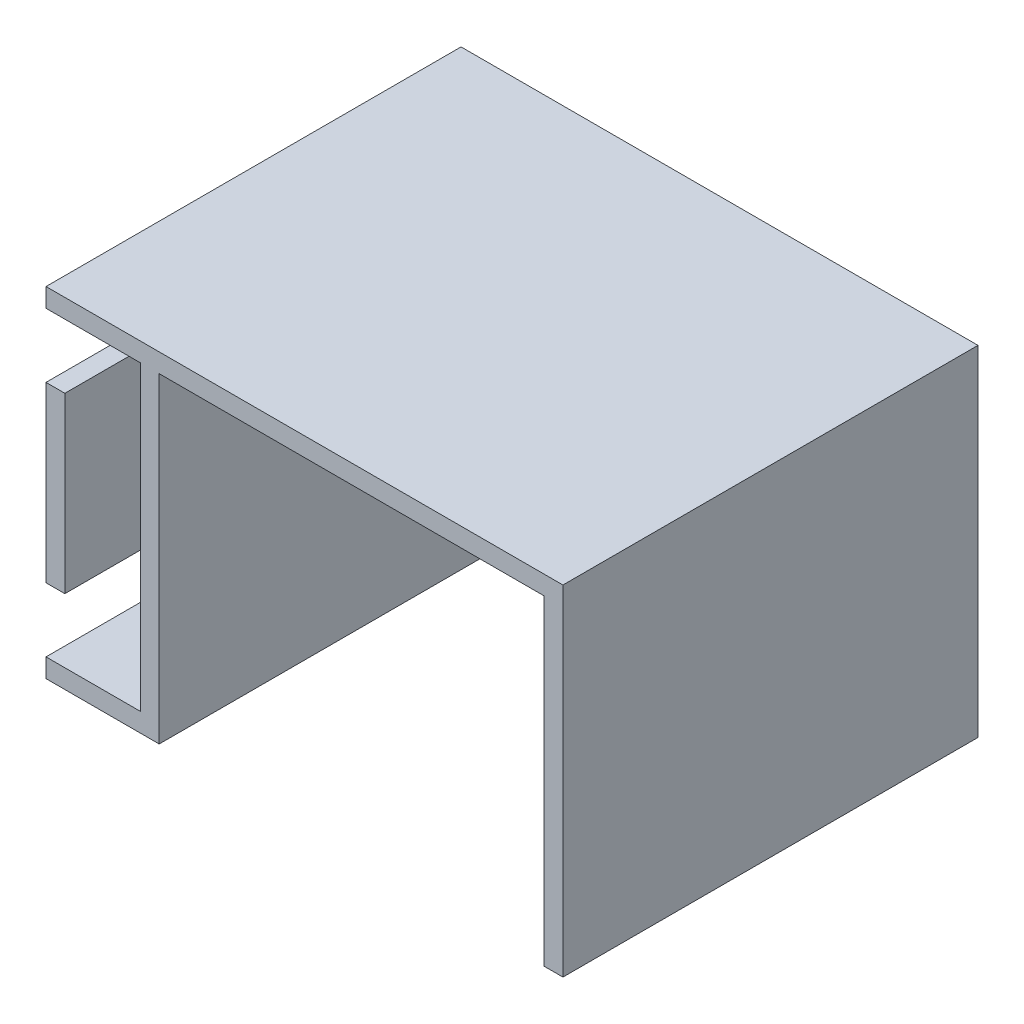
SolidWorks part; units mm, degrees
ref_plane "Front Plane" through (0, 0, 0) normal (0, 0, 1) x (1, 0, 0)
ref_plane "Top Plane" through (0, 0, 0) normal (0, 1, 0) x (1, 0, 0)
ref_plane "Right Plane" through (0, 0, 0) normal (1, 0, 0) x (0, 0, -1)
sketch "Sketch1" plane through (0, 0, 0) normal (0, 0, 1) x (1, 0, 0)
  line L1 (-10.1, -10.1) -> (10.1, -10.1)
  line L2 (-10.1, -10.1) -> (-10.1, 10.1)
  line L3 (-10.1, 10.1) -> (10.1, 10.1)
  line L4 (10.1, -10.1) -> (10.1, 10.1)
  line L5 (-10.1, -10.1) -> (10.1, 10.1) construction
  line L6 (-10.1, 10.1) -> (10.1, -10.1) construction
  point P0 (0, 0)
  dimension "D1" = 20.2
  dimension "D2" = 20.2
sketch "Sketch2" plane through (0, 0, 0) normal (0, 0, 1) x (1, 0, 0)
  line L0 (0, 0) -> (10.1, 0) construction
  line L1 (0, 0) -> (0, 10.1) construction
  line L2 (10.1, 0) -> (10.1, -10) construction
  line L4 (11.2, -6.9) -> (11.2, 11.1)
  line L5 (11.2, 11.1) -> (-11.2, 11.1)
  line L7 (-11.2, 11.1) -> (-11.2, -5.9)
  line L8 (-11.2, -5.9) -> (-15.2, -5.9)
  line L9 (-15.2, -5.9) -> (-15.2, 10.1)
  line L10 (-15.2, 10.1) -> (-16.2, 10.1)
  line L11 (-16.2, 10.1) -> (-16.2, -6.9)
  line L13 (-10.2, -6.9) -> (-16.2, -6.9)
  line L14 (-10.2, -6.9) -> (-10.2, 10.1)
  line L15 (-10.2, 10.1) -> (10.2, 10.1)
  line L16 (10.2, 10.1) -> (10.2, -6.9)
  line L19 (-10, -8.9) -> (11.2, -8.9) construction
  line L21 (10.2, -6.9) -> (11.2, -6.9)
  dimension "D2" = 20
  dimension "D3" = 18
  dimension "D4" = 22.4
  dimension "D5" = 6
  dimension "D6" = 17
  dimension "D7" = 4
  dimension "D8" = 1
  dimension "D9" = 1
  dimension "D10" = 1
  dimension "D11" = 17
  dimension "D12" = 1
  dimension "D14" = 10.1
  dimension "D15" = 10.1
extrude "Boss-Extrude2" add sketch "Sketch2" along normal blind 22 separate body
sketch "Sketch3" plane through (0, 0, 0) normal (0, 0, -1) x (-1, 0, 0)
  line L1 (15.2, 10.1) -> (11.2, 10.1)
  line L2 (15.2, 10.1) -> (15.2, -5.9)
  line L3 (15.2, -5.9) -> (11.2, -5.9)
  line L4 (11.2, 10.1) -> (11.2, -5.9)
extrude "Boss-Extrude3" add sketch "Sketch3" against normal blind 1
sketch "Sketch6" plane through (0, 0, 22) normal (0, 0, 1) x (1, 0, 0)
  line L1 (-11.2, 11.1) -> (-16.2, 11.1)
  line L2 (-11.2, 11.1) -> (-11.2, 10.1)
  line L3 (-11.2, 10.1) -> (-16.2, 10.1)
  line L4 (-16.2, 11.1) -> (-16.2, 10.1)
extrude "Boss-Extrude4" add sketch "Sketch6" against normal up to surface (22 mm away) up to face at (-3.24, 3.5, 0)
sketch "Sketch7" plane through (-16.2, 0, 0) normal (-1, 0, 0) x (0, 0, 1)
  line L0 (22, -6.9) -> (22, -5.9) construction
  line L1 (22, 11.1) -> (22, -6.9) construction
  line L3 (0, 10.1) -> (0, -10.1) construction
  line L4 (0, -5.9) -> (1, -5.9) construction
  line L5 (22, 11.1) -> (22, 10.1) construction
  line L6 (1, -5.9) -> (22, -5.9)
  line L7 (1, -5.9) -> (1, -2.5)
  line L8 (1, -2.5) -> (22, -2.5)
  line L9 (22, -5.9) -> (22, -2.5)
  line L10 (1, -2.5) -> (1, 7.6506) construction
  line L12 (22, 10.1) -> (1, 10.1)
  line L13 (22, 10.1) -> (22, 6.7)
  line L14 (22, 6.7) -> (1, 6.7)
  line L15 (1, 10.1) -> (1, 6.7)
  dimension "D1" = 1
  dimension "D2" = 1
  dimension "D3" = 1
  dimension "D4" = 3.4
  dimension "D5" = 3.4
extrude "Cut-Extrude1" cut sketch "Sketch7" against normal up to next
